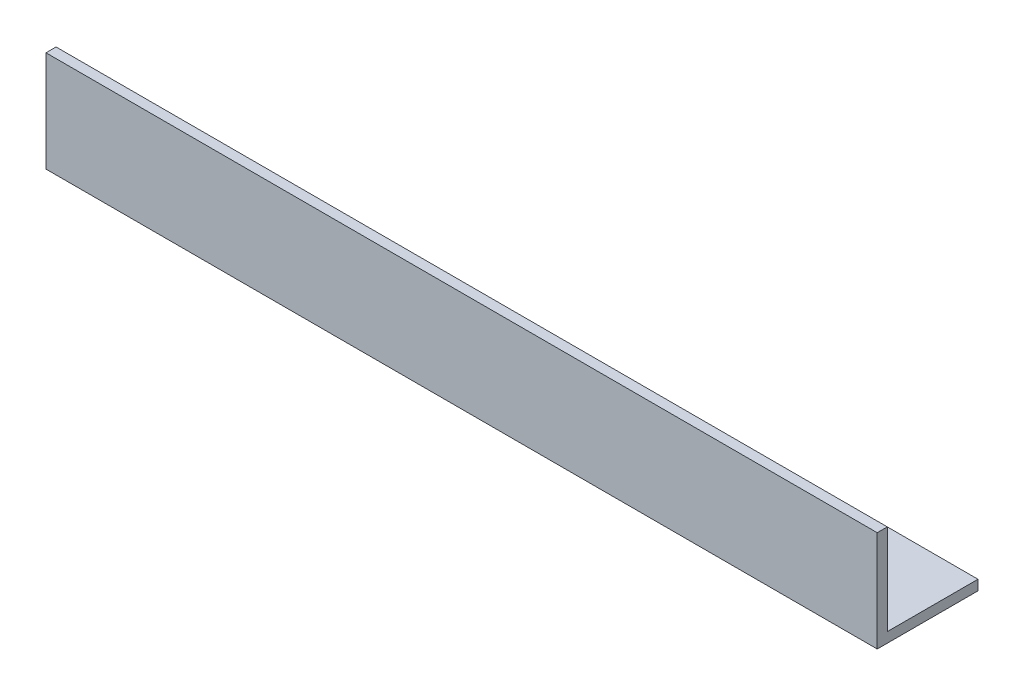
SolidWorks part; units mm, degrees
ref_plane "Front Plane" through (0, 0, 0) normal (0, 0, 1) x (1, 0, 0)
ref_plane "Top Plane" through (0, 0, 0) normal (0, 1, 0) x (1, 0, 0)
ref_plane "Right Plane" through (0, 0, 0) normal (1, 0, 0) x (0, 0, -1)
sketch "Sketch1" plane through (0, 0, 0) normal (1, 0, 0) x (0, 0, -1)
  line L0 (0, 20) -> (0, 0)
  line L1 (0, 0) -> (20, 0)
  line L2 (20, 0) -> (20, 2)
  line L3 (20, 2) -> (2, 2)
  line L4 (2, 2) -> (2, 20)
  line L5 (0, 20) -> (2, 20)
  dimension "D1" = 20
  dimension "D2" = 20
  dimension "D3" = 2
  dimension "D4" = 2
extrude "Boss-Extrude1" add sketch "Sketch1" along normal blind 165
